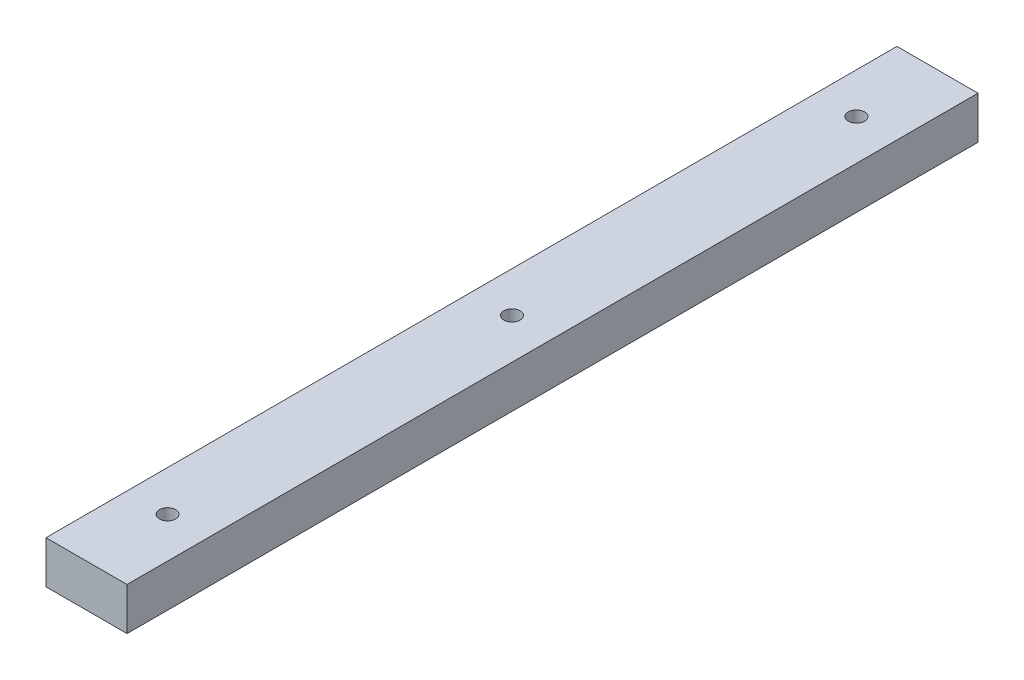
SolidWorks part; units mm, degrees
ref_plane "Front Plane" through (0, 0, 0) normal (0, 0, 1) x (1, 0, 0)
ref_plane "Top Plane" through (0, 0, 0) normal (0, 1, 0) x (1, 0, 0)
ref_plane "Right Plane" through (0, 0, 0) normal (1, 0, 0) x (0, 0, -1)
sketch "Sketch1" plane through (0, 0, 0) normal (0, 1, 0) x (1, 0, 0)
  line L0 (0, 105) -> (0, -105) construction
  line L1 (-10, -105) -> (10, -105)
  line L2 (-10, -105) -> (-10, 105)
  line L3 (-10, 105) -> (10, 105)
  line L4 (10, -105) -> (10, 105)
  line L5 (-10, -105) -> (10, 105) construction
  line L6 (-10, 105) -> (10, -105) construction
  circle A0 centre (0, 85) radius 2
  circle A1 centre (0, 0) radius 2
  circle A2 centre (0, -85) radius 2
  point P0 (0, 0)
  dimension "D3" = 4
  dimension "D4" = 20
  dimension "D5" = 20
  dimension "D1" = 210
  dimension "D2" = 20
extrude "Boss-Extrude1" add sketch "Sketch1" along normal blind 10.5
